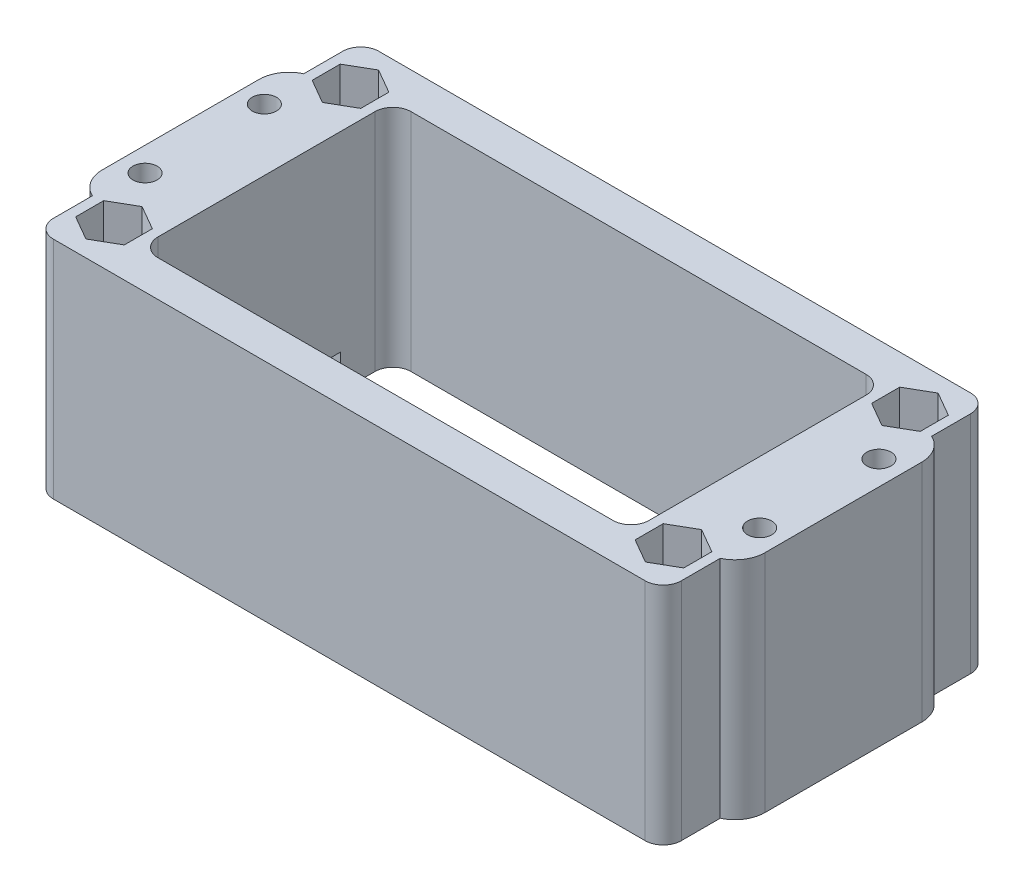
SolidWorks part; units mm, degrees
material "ABS"
ref_plane "Alzado" through (0, 0, 0) normal (0, 0, 1) x (1, 0, 0)
ref_plane "Planta" through (0, 0, 0) normal (0, 1, 0) x (1, 0, 0)
ref_plane "Vista lateral" through (0, 0, 0) normal (1, 0, 0) x (0, 0, -1)
sketch "Croquis1" plane through (0, 0, 0) normal (0, 1, 0) x (1, 0, 0)
  line L1 (1.5, 0) -> (50.6, 0)
  line L2 (0, 1.5) -> (0, 25.5)
  line L3 (1.5, 27) -> (50.6, 27)
  line L4 (52.1, 1.5) -> (52.1, 25.5)
  line L5 (7.175, 24) -> (44.925, 24)
  line L6 (5.675, 22.5) -> (5.675, 4.5)
  line L7 (7.175, 3) -> (44.925, 3)
  line L8 (46.425, 22.5) -> (46.425, 4.5)
  arc A0 (44.925, 3) -> (46.425, 4.5) centre (44.925, 4.5) ccw
  arc A1 (44.925, 24) -> (46.425, 22.5) centre (44.925, 22.5) cw
  arc A2 (7.175, 24) -> (5.675, 22.5) centre (7.175, 22.5) ccw
  arc A3 (5.675, 4.5) -> (7.175, 3) centre (7.175, 4.5) ccw
  arc A4 (50.6, 0) -> (52.1, 1.5) centre (50.6, 1.5) ccw
  arc A5 (50.6, 27) -> (52.1, 25.5) centre (50.6, 25.5) cw
  arc A6 (1.5, 0) -> (0, 1.5) centre (1.5, 1.5) cw
  arc A7 (0, 25.5) -> (1.5, 27) centre (1.5, 25.5) cw
  point P9 (5.675, 13.5)
  point P10 (0, 13.5)
  point P11 (26.05, 24)
  point P12 (26.05, 27)
  point P15 (46.425, 3)
  point P18 (46.425, 24)
  point P21 (5.675, 24)
  point P30 (0, 0)
  dimension "D5" = 1.5
  dimension "D1" = 52.1
  dimension "D2" = 27
  dimension "D3" = 21
  dimension "D4" = 40.75
extrude "Saliente-Extruir1" add sketch "Croquis1" along normal blind 18.68
sketch "Croquis2" plane through (0, 18.68, 0) normal (0, 1, 0) x (1, 0, 0)
  line L0 (0, 22.27) -> (0, 4.73)
  line L1 (0, 25.5) -> (0, 1.5) construction
  line L3 (-1.45, 20) -> (-1.45, 7)
  line L5 (26.05, 27) -> (26.05, 0) construction
  line L6 (50.6, 27) -> (1.5, 27) construction
  line L7 (1.5, 0) -> (50.6, 0) construction
  line L8 (53.55, 20) -> (53.55, 7)
  line L9 (52.1, 22.27) -> (52.1, 4.73)
  arc A1 (0, 22.27) -> (-1.45, 20) centre (1.05, 20.0012) ccw
  arc A2 (-1.45, 7) -> (0, 4.73) centre (1.05, 6.9988) ccw
  arc A3 (52.1, 22.27) -> (53.55, 20) centre (51.05, 20.0012) cw
  arc A4 (53.55, 7) -> (52.1, 4.73) centre (51.05, 6.9988) cw
  point P2 (0, 13.5)
  point P5 (0, 13.5)
  point P12 (-1.45, 13.5)
  dimension "D2" = 1.45
  dimension "D3" = 5
  dimension "D5" = 5
  dimension "D1" = 17.54
  dimension "D4" = 13
extrude "Saliente-Extruir2" add sketch "Croquis2" against normal up to surface (18.68 mm away) up to face at (26.05, 0, -13.5)
sketch "Croquis3" plane through (5.675, 0, 0) normal (1, 0, 0) x (0, 0, -1)
  line L0 (22.5, 0) -> (4.5, 0) construction
  line L1 (7.375, 0) -> (19.625, 0)
  line L2 (7.375, 0) -> (7.375, 2.83)
  line L3 (7.375, 2.83) -> (19.625, 2.83)
  line L4 (19.625, 0) -> (19.625, 2.83)
  point P6 (13.5, 0)
  point P7 (13.5, 0)
  dimension "D1" = 12.25
  dimension "D2" = 2.83
extrude "Cortar-Extruir1" cut sketch "Croquis3" against normal through all
sketch "Croquis4" plane through (0, 0, 0) normal (0, -1, 0) x (1, 0, 0)
  line L0 (2.8375, -19.625) -> (2.8375, -27) construction
  line L2 (50.6, -27) -> (1.5, -27) construction
  line L3 (5.675, -22.5) -> (0, -22.5) construction
  line L4 (0, -25.5) -> (0, -22.27) construction
  line L6 (-1.45, -19.625) -> (5.675, -19.625) construction
  line L7 (1.5, 0) -> (50.6, 0) construction
  line L8 (0, -4.73) -> (0, -1.5) construction
  line L9 (52.1, -22.27) -> (52.1, -25.5) construction
  circle A0 centre (49.26, -23.3125) radius 1.175
  circle A1 centre (2.8375, -23.3125) radius 1.175
  circle A2 centre (49.26, -3.69) radius 1.175
  circle A3 centre (2.84, -3.69) radius 1.175
  point P14 (2.8375, -22.5)
  dimension "D1" = 2.35
  dimension "D2" = 2.35
  dimension "D3" = 2.35
  dimension "D4" = 2.35
  dimension "D5" = 3.69
  dimension "D6" = 2.84
  dimension "D7" = 2.84
extrude "Cortar-Extruir2" cut sketch "Croquis4" against normal through all
sketch "Croquis5" plane through (0, 18.68, 0) normal (0, 1, 0) x (1, 0, 0)
  line L0 (26.05, 27) -> (26.05, 0) construction
  line L1 (2.8375, 25.6425) -> (0.8197, 24.4775)
  line L2 (0.8197, 24.4775) -> (0.8197, 22.1475)
  line L3 (0.8197, 22.1475) -> (2.8375, 20.9825)
  line L4 (2.8375, 20.9825) -> (4.8553, 22.1475)
  line L5 (4.8553, 22.1475) -> (4.8553, 24.4775)
  line L6 (4.8553, 24.4775) -> (2.8375, 25.6425)
  line L7 (50.6, 27) -> (1.5, 27) construction
  line L8 (1.5, 0) -> (50.6, 0) construction
  line L9 (5.675, 13.5) -> (46.425, 13.5) construction
  line L10 (5.675, 22.5) -> (5.675, 4.5) construction
  line L11 (46.425, 4.5) -> (46.425, 22.5) construction
  line L12 (47.2447, 24.4775) -> (49.2625, 25.6425)
  line L13 (47.2447, 22.1475) -> (47.2447, 24.4775)
  line L14 (49.2625, 20.9825) -> (47.2447, 22.1475)
  line L15 (51.2803, 22.1475) -> (49.2625, 20.9825)
  line L16 (51.2803, 24.4775) -> (51.2803, 22.1475)
  line L17 (49.2625, 25.6425) -> (51.2803, 24.4775)
  line L18 (49.2625, 1.3575) -> (51.2803, 2.5225)
  line L19 (51.2803, 2.5225) -> (51.2803, 4.8525)
  line L20 (51.2803, 4.8525) -> (49.2625, 6.0175)
  line L21 (49.2625, 6.0175) -> (47.2447, 4.8525)
  line L22 (47.2447, 4.8525) -> (47.2447, 2.5225)
  line L23 (47.2447, 2.5225) -> (49.2625, 1.3575)
  line L24 (4.8553, 2.5225) -> (2.8375, 1.3575)
  line L25 (4.8553, 4.8525) -> (4.8553, 2.5225)
  line L26 (2.8375, 6.0175) -> (4.8553, 4.8525)
  line L27 (0.8197, 4.8525) -> (2.8375, 6.0175)
  line L28 (0.8197, 2.5225) -> (0.8197, 4.8525)
  line L29 (2.8375, 1.3575) -> (0.8197, 2.5225)
  circle A0 centre (2.8375, 23.3125) radius 2.0178 construction
  circle A1 centre (49.2625, 23.3125) radius 2.0178 construction
  circle A2 centre (49.2625, 3.6875) radius 2.0178 construction
  circle A3 centre (2.8375, 3.6875) radius 2.0178 construction
  dimension "D1" = 4.66
extrude "Cortar-Extruir3" cut sketch "Croquis5" against normal blind 14.68
sketch "Croquis6" plane through (0, 18.68, 0) normal (0, 1, 0) x (1, 0, 0)
  line L0 (-1.45, 20) -> (-1.45, 7) construction
  line L1 (50.6, 27) -> (1.5, 27) construction
  line L2 (1.5, 0) -> (50.6, 0) construction
  line L3 (26.05, 27) -> (26.05, 0) construction
  circle A0 centre (0.55, 18.45) radius 1
  circle A1 centre (0.55, 8.55) radius 1
  circle A2 centre (51.55, 8.55) radius 1
  circle A3 centre (51.55, 18.45) radius 1
  dimension "D1" = 2
  dimension "D6" = 2
  dimension "D2" = 2
  dimension "D3" = 8.55
  dimension "D4" = 8.55
  dimension "D5" = 2
extrude "Cortar-Extruir4" cut sketch "Croquis6" against normal blind 5
